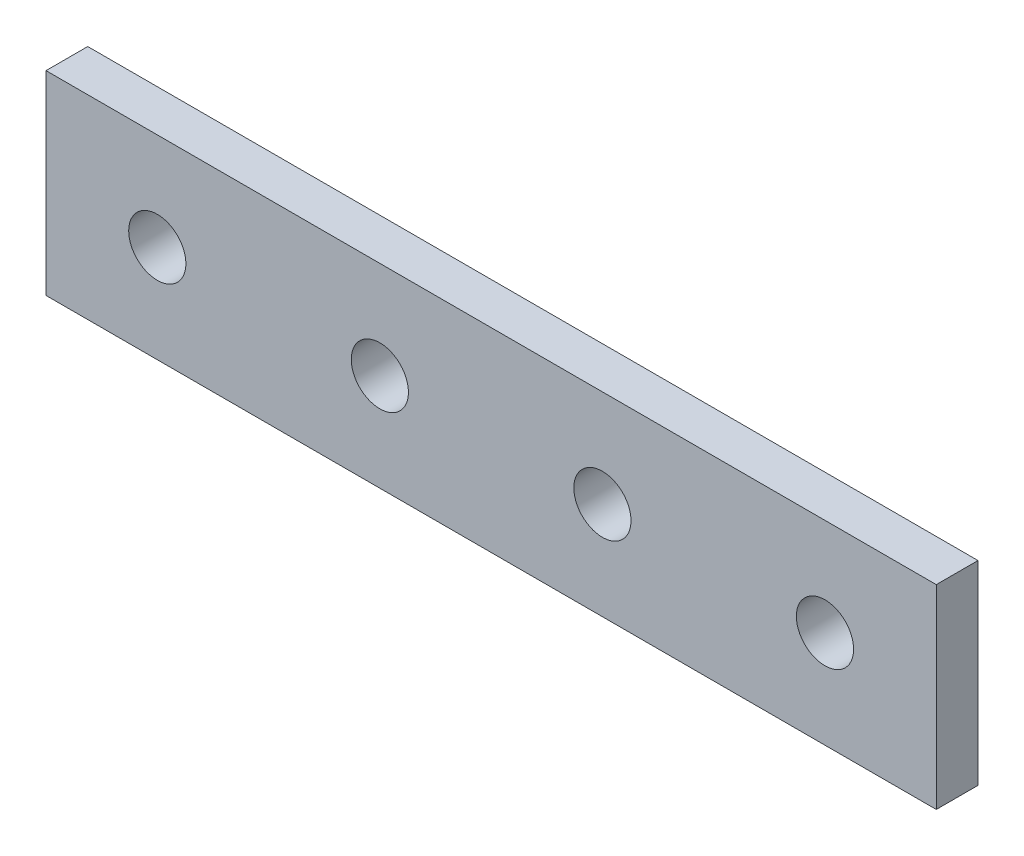
SolidWorks part; units mm, degrees
ref_plane "Front Plane" through (0, 0, 0) normal (0, 0, 1) x (1, 0, 0)
ref_plane "Top Plane" through (0, 0, 0) normal (0, 1, 0) x (1, 0, 0)
ref_plane "Right Plane" through (0, 0, 0) normal (1, 0, 0) x (0, 0, -1)
sketch "Sketch1" plane through (0, 0, 0) normal (0, 0, 1) x (1, 0, 0)
  line L0 (0, 0) -> (0, 22.225)
  line L1 (12.7, 11.1125) -> (38.1, 11.1125) construction
  line L2 (38.1, 11.1125) -> (63.5, 11.1125) construction
  line L3 (63.5, 11.1125) -> (88.9, 11.1125) construction
  line L4 (101.6, 22.225) -> (0, 22.225)
  line L5 (101.6, 0) -> (0, 0)
  line L7 (101.6, 22.225) -> (101.6, 0)
  circle A0 centre (12.7, 11.1125) radius 3.2639
  circle A1 centre (38.1, 11.1125) radius 3.2639
  circle A2 centre (63.5, 11.1125) radius 3.2639
  circle A3 centre (88.9, 11.1125) radius 3.2639
  dimension "D1" = 25.4
  dimension "E" = 6.5278
  dimension "D2" = 12.7
  dimension "C" = 22.225
  dimension "D3" = 11.1125
  dimension "B" = 101.6
extrude "Boss-Extrude1" add sketch "Sketch1" along normal mid plane 4.7625
